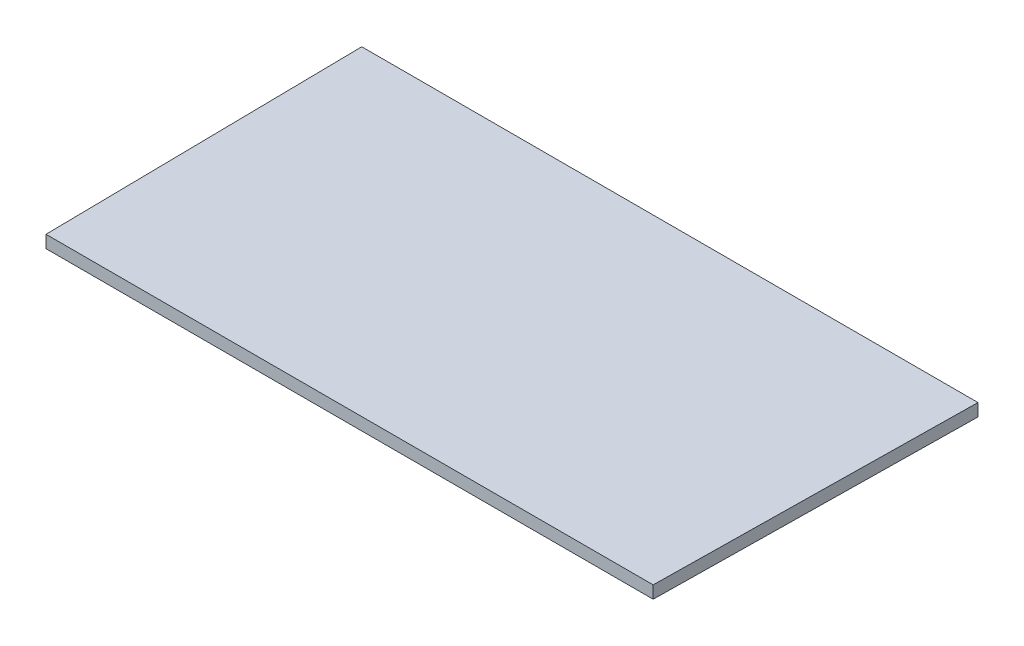
SolidWorks part; units mm, degrees
ref_plane "Front Plane" through (0, 0, 0) normal (0, 0, 1) x (1, 0, 0)
ref_plane "Top Plane" through (0, 0, 0) normal (0, 1, 0) x (1, 0, 0)
ref_plane "Right Plane" through (0, 0, 0) normal (1, 0, 0) x (0, 0, -1)
sketch "Sketch1" plane through (0, 0, 0) normal (0, 1, 0) x (1, 0, 0)
  line L0 (-72.9864, 0) -> (72.9864, 0)
  line L1 (-72.9864, 0) -> (-74.075, 77)
  line L2 (-74.075, 77) -> (74.075, 77)
  line L3 (74.075, 77) -> (72.9864, 0)
  point P4 (0, 0)
  dimension "D1" = 89.19
  dimension "D2" = 89.19
  dimension "D3" = 148.15
  dimension "D4" = 77
extrude "Boss-Extrude1" add sketch "Sketch1" along normal blind 3
